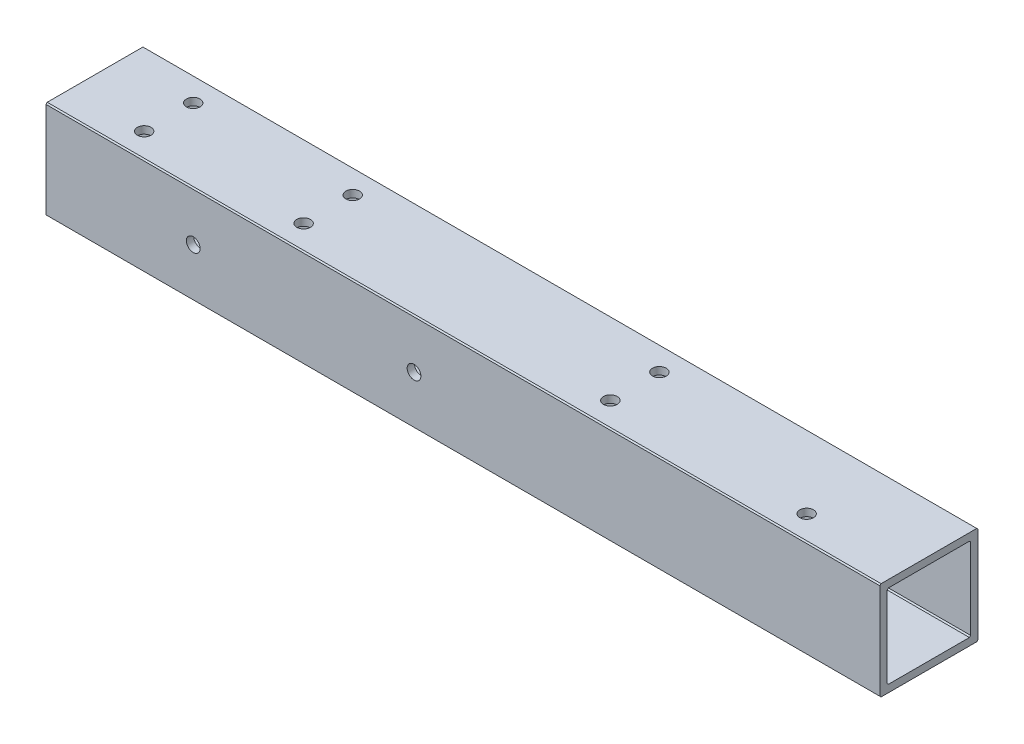
SolidWorks part; units mm, degrees
ref_plane "Front Plane" through (0, 0, 0) normal (0, 0, 1) x (1, 0, 0)
ref_plane "Top Plane" through (0, 0, 0) normal (0, 1, 0) x (1, 0, 0)
ref_plane "Right Plane" through (0, 0, 0) normal (1, 0, 0) x (0, 0, -1)
ref_plane "Plane1" through (0, 142, 0) normal (0, 1, 0) x (1, 0, 0)
sketch "Sketch1" plane through (0, 142, 0) normal (0, 1, 0) x (1, 0, 0)
  line L0 (89.85, -140) -> (89.85, -100)
  line L1 (89.85, -100) -> (-250, -100)
  line L2 (-250, -100) -> (-250, -140)
  line L3 (-250, -140) -> (89.85, -140)
extrude "Boss-Extrude1" add sketch "Sketch1" against normal blind 40
sketch "Sketch2" plane through (-250, 0, 0) normal (-1, 0, 0) x (0, 0, 1)
  line L0 (103, 105) -> (137, 105)
  line L1 (137, 105) -> (137, 139)
  line L2 (137, 139) -> (103, 139)
  line L3 (103, 139) -> (103, 105)
extrude "Cut-Extrude1" cut sketch "Sketch2" against normal through all
hole_wizard "Ø5.6 (5.6) Diameter Hole1" positions "Sketch4" profile "Sketch3" hole size "Ø5.6" standard "ANSI Metric"
sketch "Sketch4" plane through (0, 105, 0) normal (0, 1, 0) x (1, 0, 0)
  point P0 (50, -130)
  point P1 (-30, -130)
  point P2 (-30, -110)
  point P3 (-155, -130)
  point P4 (-220, -130)
  point P5 (-155, -110)
  point P6 (-220, -110)
sketch "Sketch3" plane through (50, 105, 130) normal (1, 0, 0) x (0, 0, 1)
  line L0 (0, 0) -> (0, 3)
  line L1 (0, 3) -> (2.8, 3)
  line L2 (2.8, 3) -> (2.8, 0)
  line L5 (2.8, 0) -> (0, 0)
  line L11 (0, -6.35) -> (0, 107.95) construction
  dimension "Thru Hole Dia." = 5.6
  dimension "Thru Hole Depth" = 3
hole_wizard "Ø5.6 (5.6) Diameter Hole2" positions "Sketch6" profile "Sketch5" hole size "Ø5.6" standard "ANSI Metric"
sketch "Sketch6" plane through (0, 0, 100) normal (0, 0, -1) x (-1, 0, 0)
  point P0 (100, 122)
  point P1 (190, 122)
sketch "Sketch5" plane through (-100, 122, 100) normal (1, 0, 0) x (0, 1, 0)
  line L0 (0, 0) -> (0, 3)
  line L1 (0, 3) -> (2.8, 3)
  line L2 (2.8, 3) -> (2.8, 0)
  line L5 (2.8, 0) -> (0, 0)
  line L11 (0, -6.35) -> (0, 107.95) construction
  dimension "Thru Hole Dia." = 5.6
  dimension "Thru Hole Depth" = 3
hole_wizard "Ø5.6 (5.6) Diameter Hole3" positions "Sketch8" profile "Sketch7" hole size "Ø5.6" standard "ANSI Metric"
sketch "Sketch8" plane through (0, 0, 137) normal (0, 0, -1) x (-1, 0, 0)
  point P0 (100, 122)
  point P1 (190, 122)
sketch "Sketch7" plane through (-100, 122, 137) normal (1, 0, 0) x (0, 1, 0)
  line L0 (0, 0) -> (0, 3)
  line L1 (0, 3) -> (2.8, 3)
  line L2 (2.8, 3) -> (2.8, 0)
  line L5 (2.8, 0) -> (0, 0)
  line L11 (0, -6.35) -> (0, 107.95) construction
  dimension "Thru Hole Dia." = 5.6
  dimension "Thru Hole Depth" = 3
hole_wizard "Ø5.6 (5.6) Diameter Hole4" positions "Sketch10" profile "Sketch9" hole size "Ø5.6" standard "ANSI Metric"
sketch "Sketch10" plane through (0, 142, 0) normal (0, 1, 0) x (1, 0, 0)
  point P0 (50, -130)
  point P1 (-30, -130)
  point P2 (-30, -110)
  point P3 (-155, -130)
  point P4 (-220, -130)
  point P5 (-155, -110)
  point P6 (-220, -110)
sketch "Sketch9" plane through (50, 142, 130) normal (1, 0, 0) x (0, 0, 1)
  line L0 (0, 0) -> (0, 40)
  line L1 (0, 40) -> (2.8, 40)
  line L2 (2.8, 40) -> (2.8, 0)
  line L5 (2.8, 0) -> (0, 0)
  line L11 (0, -6.35) -> (0, 107.95) construction
  dimension "Thru Hole Dia." = 5.6
  dimension "Thru Hole Depth" = 40
chamfer "Chamfer1" distance 0.5 angle 45 8 edges at (-80.075, 102, 100) (-80.075, 142, 100) (-80.075, 142, 140) (-80.075, 139, 137) (-80.075, 102, 140) (-80.075, 105, 103) (-80.075, 105, 137) (-80.075, 139, 103)
